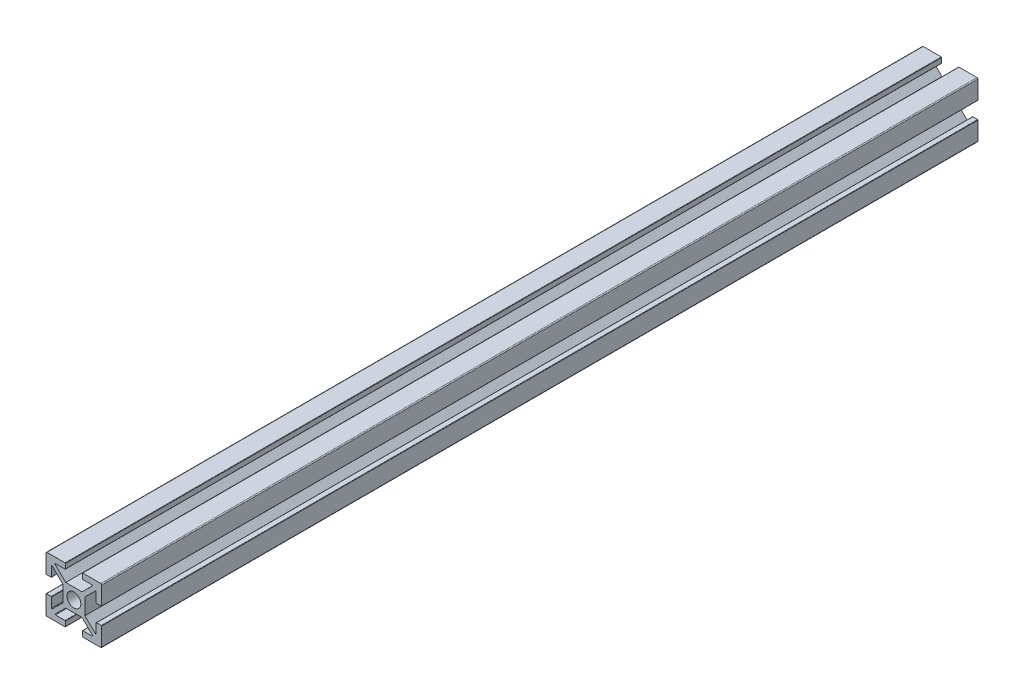
SolidWorks part; units mm, degrees
ref_plane "Front Plane" through (0, 0, 0) normal (0, 0, 1) x (1, 0, 0)
ref_plane "Top Plane" through (0, 0, 0) normal (0, 1, 0) x (1, 0, 0)
ref_plane "Right Plane" through (0, 0, 0) normal (1, 0, 0) x (0, 0, -1)
sketch "Sketch1" plane through (0, 0, 0) normal (0, 0, 1) x (1, 0, 0)
  line L0 (-31.3764, -0.0618) -> (-29.6764, -0.0618)
  line L1 (-24.6764, 6.9382) -> (-31.1764, 6.9382)
  line L2 (-31.5264, 0.0882) -> (-31.5264, 6.5882)
  line L3 (-18.5469, 0.9382) -> (-24.4133, 0.9382)
  line L4 (-25.4801, -6.0072) -> (-25.4801, -0.1164)
  line L5 (-29.5264, 0.0882) -> (-29.5264, 3.5244)
  line L6 (-28.0945, 4.9382) -> (-24.6764, 4.9382)
  line L7 (-24.5264, 5.0882) -> (-24.5264, 6.7882)
  line L8 (-29.5264, 4.9382) -> (-25.4801, 0.9382) construction
  line L9 (-29.271, 3.631) -> (-25.4801, -0.1164)
  line L10 (-28.1999, 4.6815) -> (-24.4133, 0.9382)
  line L11 (-13.4338, 4.9382) -> (-17.4801, 0.9382) construction
  line L12 (-21.4801, -3.0618) -> (-21.4801, 8.6268) construction
  line L13 (-21.4801, -3.0618) -> (-36.4642, -3.0618) construction
  line L14 (-14.7603, 4.6815) -> (-18.5469, 0.9382)
  line L15 (-13.6893, 3.631) -> (-17.4801, -0.1164)
  line L16 (-18.4338, 5.0882) -> (-18.4338, 6.7882)
  line L17 (-14.8657, 4.9382) -> (-18.2838, 4.9382)
  line L18 (-13.4338, 0.0882) -> (-13.4338, 3.5244)
  line L19 (-17.4801, -6.0072) -> (-17.4801, -0.1164)
  line L20 (-11.4338, 0.0882) -> (-11.4338, 6.5882)
  line L21 (-18.2838, 6.9382) -> (-11.7838, 6.9382)
  line L22 (-11.5838, -0.0618) -> (-13.2838, -0.0618)
  line L23 (-13.4338, -11.0618) -> (-17.4801, -7.0618) construction
  line L24 (-29.5264, -11.0618) -> (-25.4801, -7.0618) construction
  line L25 (-11.5838, -6.0618) -> (-13.2838, -6.0618)
  line L26 (-18.2838, -13.0618) -> (-11.7838, -13.0618)
  line L27 (-11.4338, -6.2118) -> (-11.4338, -12.7118)
  line L28 (-13.4338, -6.2118) -> (-13.4338, -9.648)
  line L29 (-14.8657, -11.0618) -> (-18.2838, -11.0618)
  line L30 (-18.4338, -11.2118) -> (-18.4338, -12.9118)
  line L31 (-13.6893, -9.7547) -> (-17.4801, -6.0072)
  line L32 (-14.7603, -10.8051) -> (-18.5469, -7.0618)
  line L33 (-28.1999, -10.8051) -> (-24.4133, -7.0618)
  line L34 (-29.271, -9.7547) -> (-25.4801, -6.0072)
  line L35 (-24.5264, -11.2118) -> (-24.5264, -12.9118)
  line L36 (-28.0945, -11.0618) -> (-24.6764, -11.0618)
  line L37 (-29.5264, -6.2118) -> (-29.5264, -9.648)
  line L38 (-18.5469, -7.0618) -> (-24.4133, -7.0618)
  line L39 (-31.5264, -6.2118) -> (-31.5264, -12.7118)
  line L40 (-24.6764, -13.0618) -> (-31.1764, -13.0618)
  line L41 (-31.3764, -6.0618) -> (-29.6764, -6.0618)
  circle A0 centre (-21.4801, -3.0618) radius 2.5
  arc A1 (-31.5264, 6.5882) -> (-31.1764, 6.9382) centre (-31.1764, 6.5882) cw
  arc A2 (-31.3764, -0.0618) -> (-31.5264, 0.0882) centre (-31.3764, 0.0882) cw
  arc A3 (-29.6764, -0.0618) -> (-29.5264, 0.0882) centre (-29.6764, 0.0882) ccw
  arc A4 (-24.6764, 6.9382) -> (-24.5264, 6.7882) centre (-24.6764, 6.7882) cw
  arc A5 (-24.6764, 4.9382) -> (-24.5264, 5.0882) centre (-24.6764, 5.0882) ccw
  arc A6 (-28.1999, 4.6815) -> (-28.0945, 4.9382) centre (-28.0945, 4.7882) cw
  arc A7 (-29.271, 3.631) -> (-29.5264, 3.5244) centre (-29.3764, 3.5244) ccw
  arc A8 (-13.6893, 3.631) -> (-13.4338, 3.5244) centre (-13.5838, 3.5244) cw
  arc A9 (-14.7603, 4.6815) -> (-14.8657, 4.9382) centre (-14.8657, 4.7882) ccw
  arc A10 (-18.2838, 4.9382) -> (-18.4338, 5.0882) centre (-18.2838, 5.0882) cw
  arc A11 (-18.2838, 6.9382) -> (-18.4338, 6.7882) centre (-18.2838, 6.7882) ccw
  arc A12 (-13.2838, -0.0618) -> (-13.4338, 0.0882) centre (-13.2838, 0.0882) cw
  arc A13 (-11.5838, -0.0618) -> (-11.4338, 0.0882) centre (-11.5838, 0.0882) ccw
  arc A14 (-11.4338, 6.5882) -> (-11.7838, 6.9382) centre (-11.7838, 6.5882) ccw
  arc A15 (-11.4338, -12.7118) -> (-11.7838, -13.0618) centre (-11.7838, -12.7118) cw
  arc A16 (-11.5838, -6.0618) -> (-11.4338, -6.2118) centre (-11.5838, -6.2118) cw
  arc A17 (-13.2838, -6.0618) -> (-13.4338, -6.2118) centre (-13.2838, -6.2118) ccw
  arc A18 (-18.2838, -13.0618) -> (-18.4338, -12.9118) centre (-18.2838, -12.9118) cw
  arc A19 (-18.2838, -11.0618) -> (-18.4338, -11.2118) centre (-18.2838, -11.2118) ccw
  arc A20 (-14.7603, -10.8051) -> (-14.8657, -11.0618) centre (-14.8657, -10.9118) cw
  arc A21 (-13.6893, -9.7547) -> (-13.4338, -9.648) centre (-13.5838, -9.648) ccw
  arc A22 (-29.271, -9.7547) -> (-29.5264, -9.648) centre (-29.3764, -9.648) cw
  arc A23 (-28.1999, -10.8051) -> (-28.0945, -11.0618) centre (-28.0945, -10.9118) ccw
  arc A24 (-24.6764, -11.0618) -> (-24.5264, -11.2118) centre (-24.6764, -11.2118) cw
  arc A25 (-24.6764, -13.0618) -> (-24.5264, -12.9118) centre (-24.6764, -12.9118) ccw
  arc A26 (-29.6764, -6.0618) -> (-29.5264, -6.2118) centre (-29.6764, -6.2118) cw
  arc A27 (-31.3764, -6.0618) -> (-31.5264, -6.2118) centre (-31.3764, -6.2118) ccw
  arc A28 (-31.5264, -12.7118) -> (-31.1764, -13.0618) centre (-31.1764, -12.7118) ccw
  point P27 (-18.4338, 4.9382)
  point P28 (-11.4338, -13.0618)
  point P47 (-17.4801, -3.0618)
  point P57 (-21.4801, 0.9382)
  point P59 (-18.4338, 6.9382)
  point P60 (-13.4338, -0.0618)
  point P61 (-11.4338, -0.0618)
  point P62 (-11.4338, 6.9382)
  point P112 (-25.4801, -3.0618)
  point P113 (-11.4338, -6.0618)
  point P114 (-13.4338, -6.0618)
  point P115 (-18.4338, -13.0618)
  point P116 (-21.4801, -7.0618)
  point P117 (-24.5264, -11.0618)
  point P118 (-24.5264, -13.0618)
  point P119 (-29.5264, -6.0618)
  point P120 (-18.4338, -11.0618)
  point P121 (-31.5264, -6.0618)
  point P122 (-31.5264, -13.0618)
  dimension "D3" = 0.35
  dimension "D4" = 0.15
  dimension "D5" = 0.15
  dimension "D6" = 0.15
  dimension "D7" = 0.15
  dimension "D8" = 0.15
  dimension "D9" = 0.15
  dimension "D1" = 0.75
  dimension "D2" = 0.75
extrude "Boss-Extrude1" add sketch "Sketch1" along normal blind 315.81
